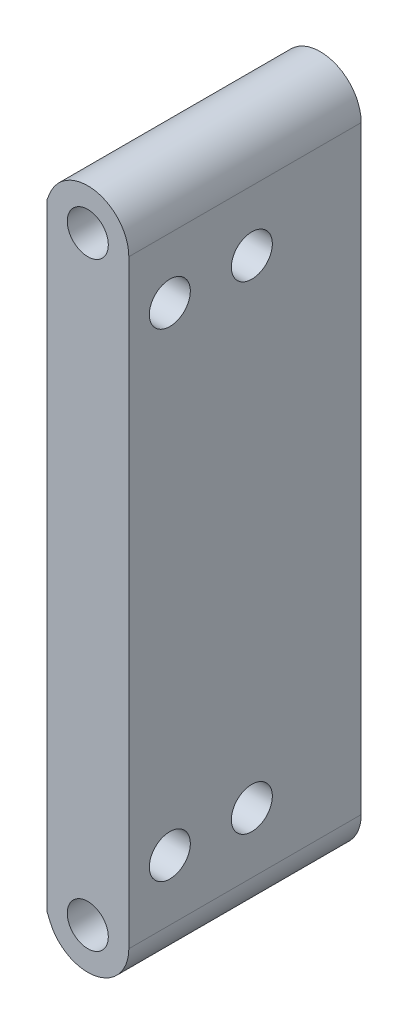
SolidWorks part; units mm, degrees
ref_plane "前视基准面" through (0, 0, 0) normal (0, 0, 1) x (1, 0, 0)
ref_plane "上视基准面" through (0, 0, 0) normal (0, 1, 0) x (1, 0, 0)
ref_plane "右视基准面" through (0, 0, 0) normal (1, 0, 0) x (0, 0, -1)
other "Configuration Table"
sketch "草图1" plane through (0, 0, 0) normal (0, 0, 1) x (1, 0, 0)
  line L4 (-31, 0) -> (0, 0) construction
  line L6 (-24.6919, 23.0684) -> (-33.7716, 1.1481)
  line L11 (-18.9203, -21.9203) -> (-18.9203, 21.9203)
  line L13 (-24.6919, -23.0684) -> (-33.7716, -1.1481)
  circle A0 centre (0, 0) radius 31 construction
  circle A1 centre (-31, 0) radius 1.5
  circle A2 centre (-21.9203, 21.9203) radius 1.5
  circle A3 centre (0, 31) radius 1.5 construction
  circle A4 centre (21.9203, 21.9203) radius 1.5 construction
  circle A5 centre (31, 0) radius 1.5 construction
  circle A6 centre (21.9203, -21.9203) radius 1.5 construction
  circle A7 centre (0, -31) radius 1.5 construction
  circle A8 centre (-21.9203, -21.9203) radius 1.5
  arc A9 (-24.6919, 23.0684) -> (-18.9203, 21.9203) centre (-21.9203, 21.9203) cw
  arc A10 (-24.6919, -23.0684) -> (-18.9203, -21.9203) centre (-21.9203, -21.9203) ccw
  arc A11 (-33.7716, 1.1481) -> (-33.7716, -1.1481) centre (-31, 0) ccw
  point P18 (0, 0)
  dimension "D2" = 62
  dimension "D3" = 3
  dimension "D4" = 3
  dimension "D5" = 3
  dimension "D1" = 8
extrude "凸台-拉伸1" add sketch "草图1" along normal blind 17
sketch "草图3" plane through (0, 0, 17) normal (0, 0, 1) x (1, 0, 0)
  line L0 (-24.6919, 23.0684) -> (-33.7716, 1.1481) construction
  line L1 (-24.9203, 22.517) -> (-34, 22.517)
  line L2 (-24.9203, 22.517) -> (-24.9203, -22.517)
  line L3 (-24.9203, -22.517) -> (-34, -22.517)
  line L4 (-34, 22.517) -> (-34, -22.517)
  line L5 (-33.7716, -1.1481) -> (-24.6919, -23.0684) construction
  line L6 (-18.9203, -21.9203) -> (-18.9203, 21.9203) construction
  arc A0 (-33.7716, 1.1481) -> (-33.7716, -1.1481) centre (-31, 0) ccw construction
  dimension "D1" = 6
extrude "切除-拉伸2" cut sketch "草图3" against normal blind 12
sketch "草图5" plane through (-24.9203, 0, 0) normal (-1, 0, 0) x (0, 0, 1)
  line L0 (17, 0) -> (5, 0) construction
  line L1 (17, -22.517) -> (17, 22.517) construction
  line L2 (5, -1.1481) -> (5, 1.1481) construction
  line L3 (11, 0) -> (11, 22.517) construction
  line L4 (5, 22.517) -> (17, 22.517) construction
  circle A0 centre (8, 17.5) radius 1.5
  circle A1 centre (14, 17.5) radius 1.5
  circle A2 centre (14, -17.5) radius 1.5
  circle A3 centre (8, -17.5) radius 1.5
  dimension "D1" = 3
  dimension "D2" = 6
  dimension "D3" = 35
extrude "切除-拉伸3" cut sketch "草图5" against normal through all
